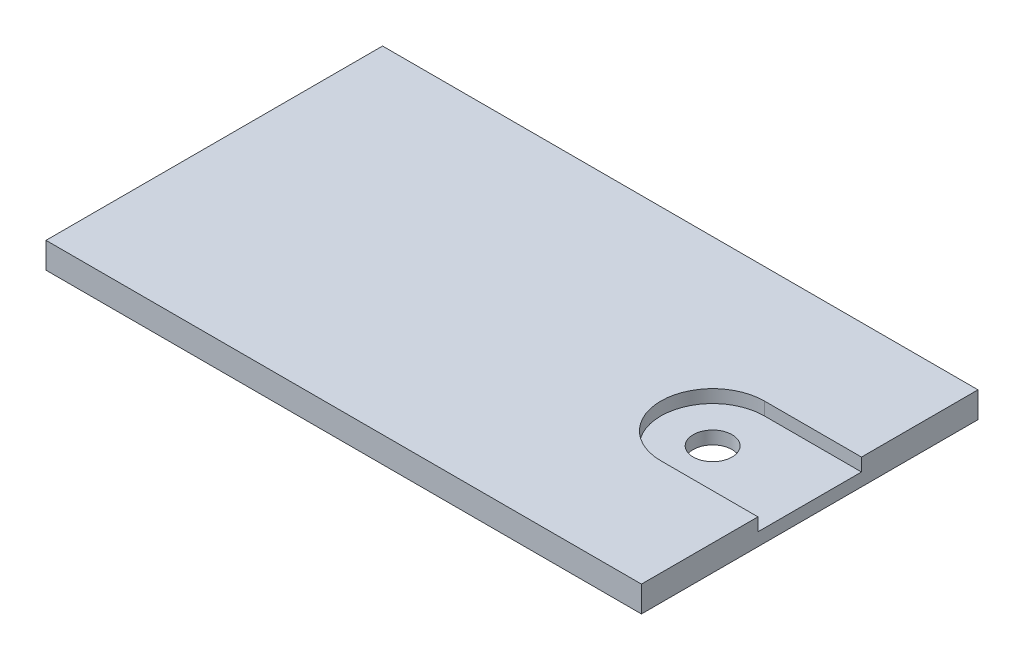
SolidWorks part; units mm, degrees
ref_plane "Front Plane" through (0, 0, 0) normal (0, 0, 1) x (1, 0, 0)
ref_plane "Top Plane" through (0, 0, 0) normal (0, 1, 0) x (1, 0, 0)
ref_plane "Right Plane" through (0, 0, 0) normal (1, 0, 0) x (0, 0, -1)
sketch "Sketch1" plane through (0, 0, 0) normal (0, 1, 0) x (1, 0, 0)
  line L1 (0, 0) -> (46, 0)
  line L2 (0, 0) -> (0, 26)
  line L3 (0, 26) -> (46, 26)
  line L4 (46, 0) -> (46, 26)
  dimension "D1" = 26
  dimension "D2" = 46
extrude "Boss-Extrude1" add sketch "Sketch1" along normal blind 2
sketch "Sketch2" plane through (0, 2, 0) normal (0, 1, 0) x (1, 0, 0)
  line L0 (38.5, 13) -> (53.5, 13) construction
  line L1 (38.5, 17) -> (53.5, 17)
  line L2 (38.5, 9) -> (53.5, 9)
  line L3 (46, 0) -> (46, 26) construction
  arc A0 (38.5, 17) -> (38.5, 9) centre (38.5, 13) ccw
  arc A1 (53.5, 9) -> (53.5, 17) centre (53.5, 13) ccw
  point P2 (46, 13)
  point P7 (0, 0)
  point P10 (46, 13)
extrude "Cut-Extrude1" cut sketch "Sketch2" against normal blind 1
hole_wizard "Ø3.0mm Dowel Hole1" positions "3DSketch1" profile "Sketch3" hole size "Ø3.0" standard "BSI" end condition up to next
sketch3d "3DSketch1"
  line L0 (38.5, 1, -13) -> (38.5, 2, -13) construction
  point P2 (38.5, 1, -13)
  point P6 (65.1579, 32.1445, 0)
  point P9 (0, 0, 0)
sketch "Sketch3" plane through (38.5, 1, -13) normal (1, 0, 0) x (0, 0, 1)
  line L0 (0, 0) -> (0, 1)
  line L1 (0, 1) -> (1.5, 1)
  line L2 (1.5, 1) -> (1.5, 0)
  line L5 (1.5, 0) -> (0, 0)
  line L11 (0, -6.35) -> (0, 107.95) construction
  dimension "Thru Hole Dia." = 3
  dimension "Thru Hole Depth" = 1
